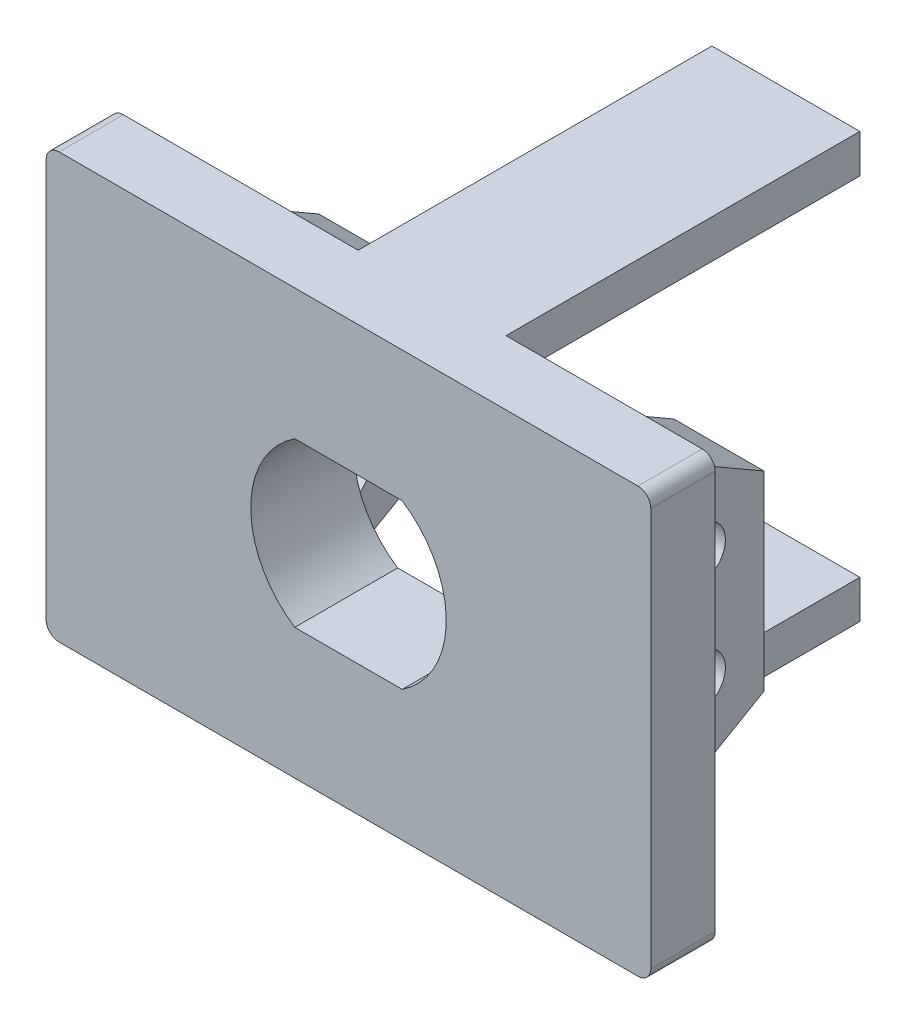
SolidWorks part; units mm, degrees
material "ABS"
ref_plane "Płaszczyzna przednia" through (0, 0, 0) normal (0, 0, 1) x (1, 0, 0)
ref_plane "Płaszczyzna górna" through (0, 0, 0) normal (0, 1, 0) x (1, 0, 0)
ref_plane "Płaszczyzna prawa" through (0, 0, 0) normal (1, 0, 0) x (0, 0, -1)
sketch "Szkic1" plane through (0, 0, 0) normal (0, 0, 1) x (1, 0, 0)
  line L0 (-4.1758, 6.35) -> (4.1758, 6.35)
  line L1 (-23.5, -16.5) -> (23.5, -16.5)
  line L2 (-23.5, -16.5) -> (-23.5, 16.5)
  line L3 (-23.5, 16.5) -> (23.5, 16.5)
  line L4 (23.5, -16.5) -> (23.5, 16.5)
  line L5 (-23.5, -16.5) -> (23.5, 16.5) construction
  line L6 (-23.5, 16.5) -> (23.5, -16.5) construction
  line L7 (-4.1758, -6.35) -> (4.1758, -6.35)
  circle A0 centre (0, 0) radius 7.6
  point P0 (0, 0)
  dimension "D3" = 15.2
  dimension "D1" = 33
  dimension "D2" = 47
  dimension "D4" = 12.7
extrude "Dodanie-wyciągnięcie1" add sketch "Szkic1" along normal blind 5 contours L0 A0 | L7 A0 | L1 L4 L3 L2 A0
sketch "Szkic2" plane through (0, 0, 0) normal (0, 0, -1) x (-1, 0, 0)
  line L0 (23.5, -16.5) -> (-23.5, -16.5) construction
  line L1 (-17.3, -10.3) -> (-10.3, -10.3)
  line L2 (-17.3, -10.3) -> (-17.3, 10.3)
  line L3 (-17.3, 10.3) -> (-10.3, 10.3)
  line L4 (-10.3, -10.3) -> (-10.3, 10.3)
  line L5 (-17.3, -10.3) -> (-10.3, 10.3) construction
  line L6 (-17.3, 10.3) -> (-10.3, -10.3) construction
  line L7 (10.3, -10.3) -> (17.3, -10.3)
  line L8 (10.3, -10.3) -> (10.3, 10.3)
  line L9 (10.3, 10.3) -> (17.3, 10.3)
  line L10 (17.3, -10.3) -> (17.3, 10.3)
  line L11 (10.3, -10.3) -> (17.3, 10.3) construction
  line L12 (10.3, 10.3) -> (17.3, -10.3) construction
  line L14 (-23.5, 16.5) -> (23.5, 16.5) construction
  line L15 (-23.5, -16.5) -> (-23.5, 16.5) construction
  line L16 (23.5, 16.5) -> (23.5, -16.5) construction
  point P0 (-13.8, 0)
  point P5 (13.8, 0)
  dimension "D1" = 6.2
  dimension "D2" = 7
  dimension "D3" = 6.2
  dimension "D4" = 6.2
  dimension "D5" = 6.2
extrude "Dodanie-wyciągnięcie2" add sketch "Szkic2" along normal blind 10
chamfer "Sfazowanie1" distance 5 angle 30 4 edges at (13.8, 10.3, -10) (-13.8, 10.3, -10) (-13.8, -10.3, -10) (13.8, -10.3, -10)
sketch "Szkic3" plane through (17.3, 0, 0) normal (1, 0, 0) x (0, 0, -1)
  line L0 (0, -16.5) -> (0, 16.5) construction
  line L1 (5, -10.3) -> (0, -10.3) construction
  line L2 (5, 10.3) -> (0, 10.3) construction
  circle A0 centre (5, 4.3) radius 2
  circle A1 centre (5, -4.3) radius 2
  dimension "D1" = 4
  dimension "D2" = 5
  dimension "D3" = 6
  dimension "D4" = 6
extrude "Wytnij-wyciągnięcie1" cut sketch "Szkic3" against normal through all
fillet "Zaokrąglenie1" radius 1 4 edges at (-23.5, -16.5, 2.5) (23.5, -16.5, 2.5) (-23.5, 16.5, 2.5) (23.5, 16.5, 2.5)
sketch "Szkic4" plane through (0, 0, 0) normal (0, 0, -1) x (-1, 0, 0)
  line L0 (-22.5, 16.5) -> (22.5, 16.5) construction
  line L1 (-7.25, 16.5) -> (4.25, 16.5)
  line L2 (-7.25, 16.5) -> (-7.25, 13.5)
  line L3 (-7.25, 13.5) -> (4.25, 13.5)
  line L4 (4.25, 16.5) -> (4.25, 13.5)
  line L5 (-23.5, -15.5) -> (-23.5, 15.5) construction
  line L7 (23.5, 15.5) -> (23.5, -15.5) construction
  line L8 (22.5, -16.5) -> (-22.5, -16.5) construction
  line L9 (-7.25, -16.5) -> (4.75, -16.5)
  line L10 (-7.25, -16.5) -> (-7.25, -13.5197)
  line L11 (-7.25, -13.5197) -> (4.75, -13.5197)
  line L12 (4.75, -16.5) -> (4.75, -13.5197)
  dimension "D1" = 3
  dimension "D2" = 19.25
  dimension "D3" = 16.25
  dimension "D4" = 2.9803
  dimension "D5" = 12
extrude "Dodanie-wyciągnięcie3" add sketch "Szkic4" along normal blind 27.5
sketch "Szkic5" plane through (0, 0, 0) normal (0, 0, -1) x (-1, 0, 0)
  line L0 (4.1758, -6.35) -> (-4.1758, -6.35) construction
  line L1 (4.1758, 6.35) -> (-4.1758, 6.35) construction
  line L2 (4.1758, -6.35) -> (-4.1758, -6.35)
  line L3 (4.1758, 6.35) -> (-4.1758, 6.35)
  line L4 (-10.3, 10.3) -> (-10.3, -10.3)
  line L5 (-10.3, -10.3) -> (10.3, -10.3)
  line L6 (10.3, -10.3) -> (10.3, 10.3)
  line L7 (10.3, 10.3) -> (-10.3, 10.3)
  arc A0 (4.1758, -6.35) -> (4.1758, 6.35) centre (0, 0) ccw construction
  arc A1 (-4.1758, 6.35) -> (-4.1758, -6.35) centre (0, 0) ccw construction
  arc A2 (4.1758, -6.35) -> (4.1758, 6.35) centre (0, 0) ccw
  arc A3 (-4.1758, 6.35) -> (-4.1758, -6.35) centre (0, 0) ccw
extrude "Dodanie-wyciągnięcie4" add sketch "Szkic5" along normal blind 3
